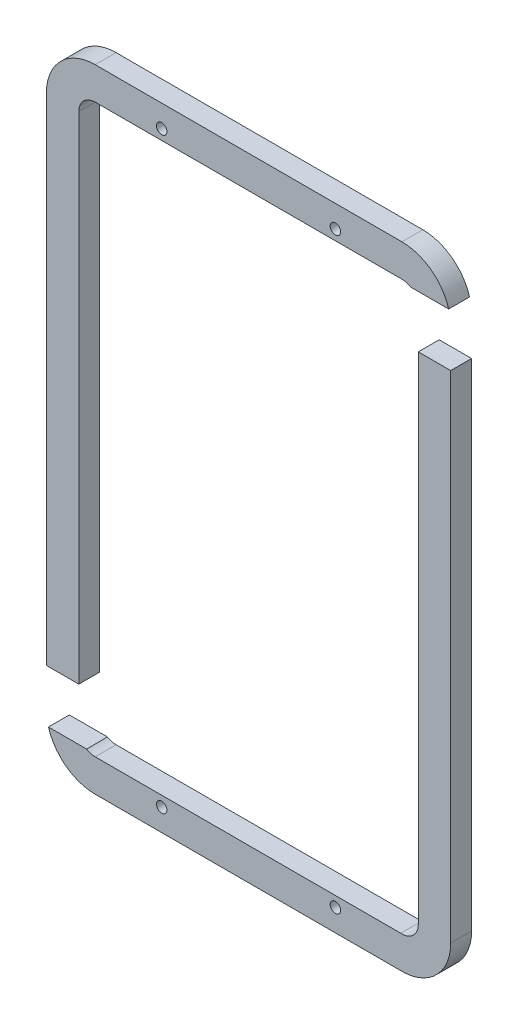
SolidWorks part; units mm, degrees
material "Maple"
ref_plane "Alzado" through (0, 0, 0) normal (0, 0, 1) x (1, 0, 0)
ref_plane "Planta" through (0, 0, 0) normal (0, 1, 0) x (1, 0, 0)
ref_plane "Vista lateral" through (0, 0, 0) normal (1, 0, 0) x (0, 0, -1)
sketch "Sketch1" plane through (0, 0, 0) normal (0, 0, 1) x (1, 0, 0)
  line L0 (-61.2229, -65.65) -> (-61.2229, 76.66)
  line L1 (-47.2229, 90.66) -> (40.7971, 90.66)
  line L2 (54.7971, 65.66) -> (54.7971, -76.65)
  line L3 (40.2171, -90.65) -> (-47.2229, -90.65)
  line L4 (-60.6393, -80.65) -> (-49.6927, -80.65)
  line L6 (-47.2229, -81.3511) -> (40.4612, -81.3511)
  line L7 (45.4982, 76.66) -> (45.4982, -76.65) construction
  line L8 (-51.9239, -65.65) -> (-51.9239, 76.66)
  line L9 (-47.2229, 81.3611) -> (40.7971, 81.3611)
  line L10 (45.4982, 65.66) -> (45.4982, -76.65)
  line L11 (43.267, 80.66) -> (54.2135, 80.66)
  line L12 (45.4982, 65.66) -> (54.7971, 65.66)
  line L13 (54.7971, 76.66) -> (54.7971, -76.65) construction
  line L14 (-61.2229, -65.65) -> (-51.9239, -65.65)
  line L16 (0, 0) -> (-9.3796, 0) construction
  line L17 (54.2135, 80.66) -> (54.7971, 65.66) construction
  line L19 (54.7971, -76.65) -> (54.9307, 13.4817) construction
  line L20 (45.4982, -76.65) -> (45.6318, 13.4954) construction
  line L21 (-47.2229, -81.3511) -> (40.4612, -81.3511) construction
  line L22 (-47.2229, -90.65) -> (40.2171, -90.65) construction
  line L23 (-61.2229, -76.65) -> (-61.2229, -65.65) construction
  line L24 (-51.9239, -76.65) -> (-51.9239, -65.65) construction
  arc A0 (40.2171, -90.65) -> (54.7971, -76.65) centre (40.7971, -76.662) ccw
  arc A1 (-61.2229, 76.66) -> (-47.2229, 90.66) centre (-47.2229, 76.66) cw
  arc A2 (-47.2229, -90.65) -> (-60.6393, -80.65) centre (-47.2229, -76.65) cw
  arc A3 (40.7971, 90.66) -> (54.2135, 80.66) centre (40.7971, 76.66) cw
  arc A4 (-51.9239, 76.66) -> (-47.2229, 81.3611) centre (-47.2229, 76.66) cw
  arc A5 (40.7971, 81.3611) -> (43.267, 80.66) centre (40.7971, 76.66) cw
  arc A6 (40.4612, -81.3511) -> (45.4982, -76.65) centre (40.7971, -76.662) ccw
  arc A7 (-47.2229, -81.3511) -> (-49.6927, -80.65) centre (-47.2229, -76.65) cw
  arc A8 (-47.2229, -81.3511) -> (-51.924, -76.65) centre (-47.2229, -76.65) cw construction
  arc A9 (-47.2229, -90.65) -> (-61.2229, -76.65) centre (-47.2229, -76.65) cw construction
  arc A10 (40.7971, 81.3611) -> (45.4982, 76.66) centre (40.7971, 76.66) cw construction
  arc A11 (40.7971, 90.66) -> (54.7971, 76.66) centre (40.7971, 76.66) cw construction
  circle A12 centre (21.7171, 84.31) radius 1.5
  circle A13 centre (-28.1429, 84.31) radius 1.5
  circle A14 centre (-28.1429, -84.31) radius 1.5
  circle A15 centre (21.7171, -84.31) radius 1.5
  point P6 (40.7971, -81.3511)
  point P11 (-61.2229, 90.66)
  point P13 (40.7971, -81.3511)
  point P49 (0, 0)
  point P50 (0, 0)
  point P51 (0, 0)
  dimension "D3" = 14
  dimension "D5" = 14
  dimension "D16" = 3
  dimension "D18" = 6.35
  dimension "D20" = 33.08
  dimension "D1" = 181.31
  dimension "D2" = 116.02
  dimension "D4" = 10
  dimension "D7" = 51.9239
  dimension "D8" = 90.66
  dimension "D9" = 87.44
  dimension "D10" = 13.4164
  dimension "D11" = 14
  dimension "D12" = 10
  dimension "D13" = 156.31
  dimension "D14" = 156.31
  dimension "D17" = 33.08
  dimension "D19" = 6.35
  dimension "D6" = 9.2989
extrude "Boss-Extrude1" add sketch "Sketch1" along normal blind 6
